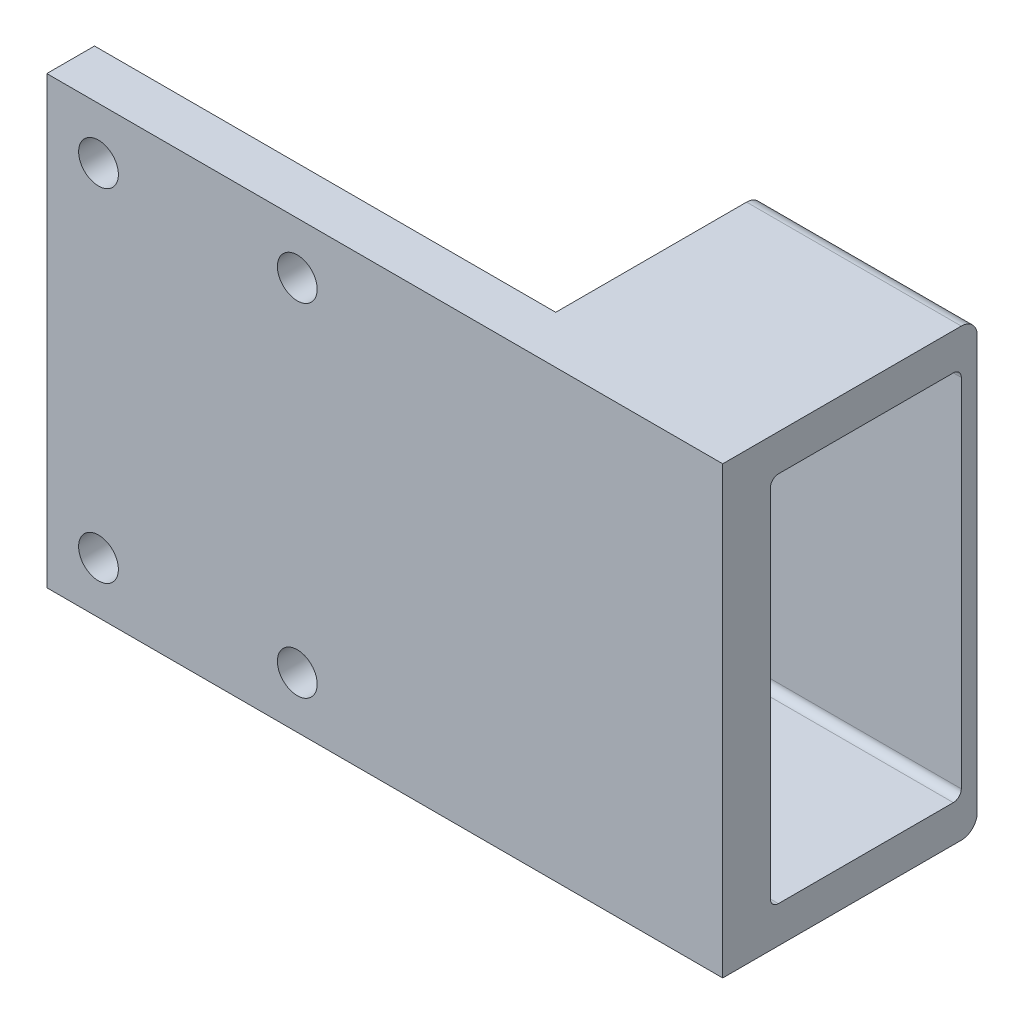
SolidWorks part; units mm, degrees
ref_plane "Plan de face" through (0, 0, 0) normal (0, 0, 1) x (1, 0, 0)
ref_plane "Plan de dessus" through (0, 0, 0) normal (0, 1, 0) x (1, 0, 0)
ref_plane "Plan de droite" through (0, 0, 0) normal (1, 0, 0) x (0, 0, -1)
sketch "Esquisse1" plane through (0, 0, 0) normal (0, 0, 1) x (1, 0, 0)
  line L1 (0, 0) -> (-42.5, 0)
  line L2 (0, 0) -> (0, -28)
  line L3 (0, -28) -> (-42.5, -28)
  line L4 (-42.5, 0) -> (-42.5, -28)
  dimension "D1" = 42.5
  dimension "D2" = 28
extrude "Boss.-Extru.1" add sketch "Esquisse1" along normal blind 3
sketch "Esquisse2" plane through (0, 0, 0) normal (0, 0, -1) x (-1, 0, 0)
  line L0 (42.5, -28) -> (0, -28) construction
  line L5 (42.5, 0) -> (42.5, -28) construction
  line L6 (46.5247, -14) -> (-2.5379, -14) construction
  circle A0 centre (39.25, -24.75) radius 1.25
  circle A1 centre (26.75, -24.75) radius 1.25
  circle A2 centre (39.25, -3.25) radius 1.25
  circle A3 centre (26.75, -3.25) radius 1.25
  point P9 (42.5, -14)
  dimension "D2" = 2.5
  dimension "D3" = 3.25
  dimension "D5" = 2.5
  dimension "D7" = 3.25
  dimension "D4" = 3.25
  dimension "D6" = 15.75
extrude "Enlèv. mat.-Extru.1" cut sketch "Esquisse2" against normal blind 3
sketch "Esquisse3" plane through (0, 0, 0) normal (0, 0, -1) x (-1, 0, 0)
  line L0 (42.5, -28) -> (0, -28) construction
  line L1 (0, 0) -> (13.5, 0)
  line L2 (0, 0) -> (0, -28)
  line L3 (0, -28) -> (13.5, -28)
  line L4 (13.5, 0) -> (13.5, -28)
  line L5 (42.5, 0) -> (42.5, -28) construction
  dimension "D1" = 29
extrude "Boss.-Extru.2" add sketch "Esquisse3" along normal blind 13
sketch "Esquisse4" plane through (-13.5, 0, 0) normal (-1, 0, 0) x (0, 0, 1)
  line L1 (-12, -2.3) -> (0, -2.3)
  line L2 (-12, -2.3) -> (-12, -25.7)
  line L3 (-12, -25.7) -> (0, -25.7)
  line L4 (0, -2.3) -> (0, -25.7)
  line L5 (-13, 0) -> (0, 0) construction
  line L7 (0, -28) -> (0, 0) construction
  dimension "D1" = 23.4
  dimension "D2" = 2.3
  dimension "D3" = 0
  dimension "D4" = 12
extrude "Enlèv. mat.-Extru.2" cut sketch "Esquisse4" against normal through all
fillet "Congé1" radius 0.5 4 edges at (-6.75, -2.3, -12) (-6.75, -25.7, -12) (-6.75, -25.7, 0) (-6.75, -2.3, 0)
fillet "Congé2" radius 1 2 edges at (-6.75, -28, -13) (-6.75, 0, -13)
